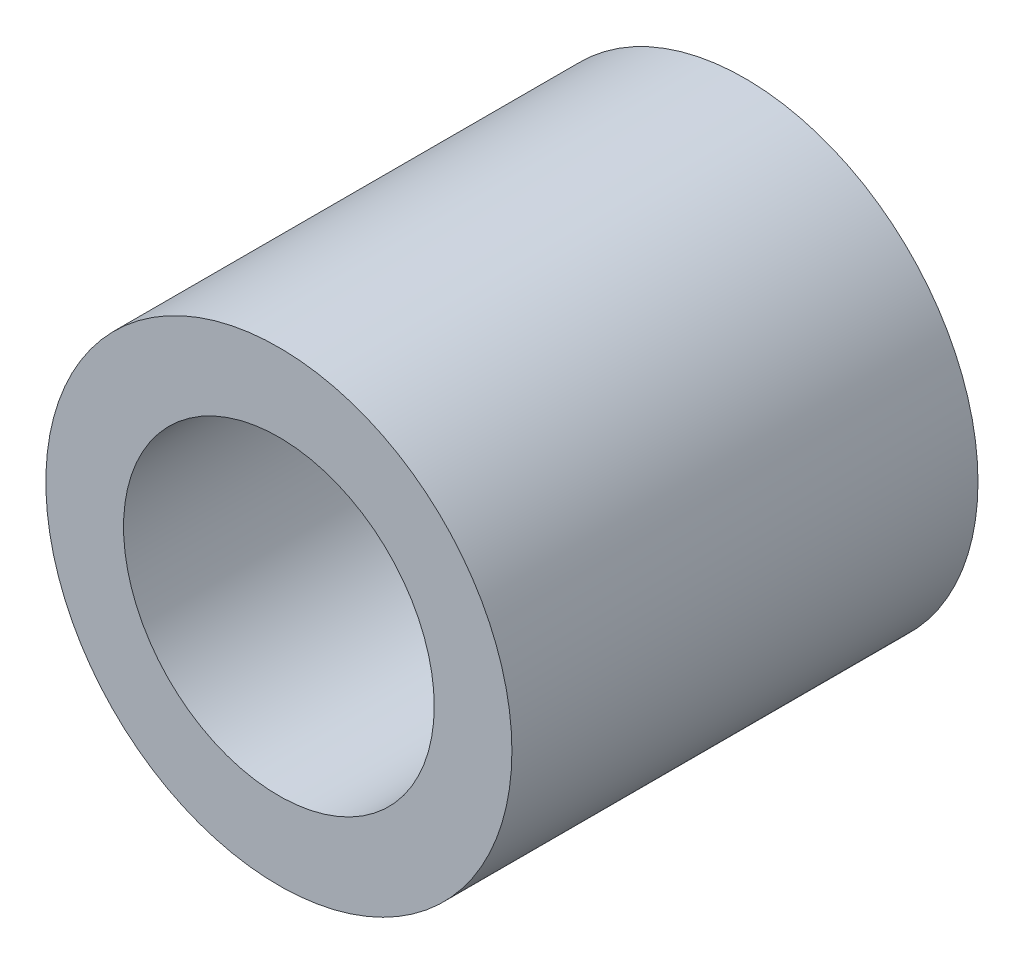
SolidWorks part; units mm, degrees
ref_plane "Front Plane" through (0, 0, 0) normal (0, 0, 1) x (1, 0, 0)
ref_plane "Top Plane" through (0, 0, 0) normal (0, 1, 0) x (1, 0, 0)
ref_plane "Right Plane" through (0, 0, 0) normal (1, 0, 0) x (0, 0, -1)
sketch "Sketch1" plane through (0, 0, 0) normal (0, 0, 1) x (1, 0, 0)
  circle A0 centre (0, 0) radius 3
  circle A1 centre (0, 0) radius 4.5
  dimension "D1" = 6
  dimension "D2" = 9
extrude "Boss-Extrude1" add sketch "Sketch1" along normal blind 9
